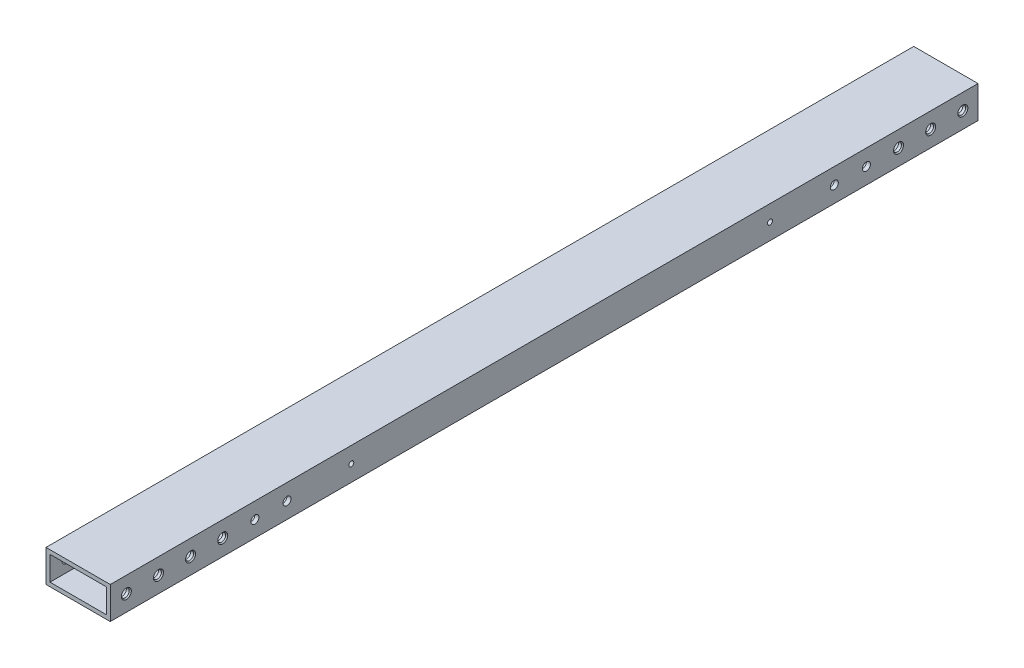
SolidWorks part; units mm, degrees
material "6061 Alloy"
ref_plane "Front Plane" through (0, 0, 0) normal (0, 0, 1) x (1, 0, 0)
ref_plane "Top Plane" through (0, 0, 0) normal (0, 1, 0) x (1, 0, 0)
ref_plane "Right Plane" through (0, 0, 0) normal (1, 0, 0) x (0, 0, -1)
sketch "Sketch1" plane through (0, 0, 0) normal (0, 0, 1) x (1, 0, 0)
  line L0 (-22.225, 9.525) -> (22.225, 9.525)
  line L2 (-25.4, 12.7) -> (25.4, 12.7)
  line L3 (-25.4, 12.7) -> (-25.4, -12.7)
  line L4 (-25.4, -12.7) -> (25.4, -12.7)
  line L5 (25.4, 12.7) -> (25.4, -12.7)
  line L10 (22.225, 9.525) -> (22.225, -9.525)
  line L11 (-22.225, -9.525) -> (22.225, -9.525)
  line L12 (-22.225, 9.525) -> (-22.225, -9.525)
  point P12 (0, 12.7)
  point P14 (25.4, 0)
  dimension "Wall Thickness" = 3.175
  dimension "Outside Width" = 50.8
  dimension "Outside Height" = 25.4
  dimension "Inside Height" = 19.05
  dimension "Inside Width" = 44.45
sketch "Sketch2" plane through (0, 0, 0) normal (1, 0, 0) x (0, 0, -1)
  line L0 (342.9, 0) -> (-342.9, 0)
  point P4 (0, 0)
  point P7 (-342.9, 0)
  point P10 (342.9, 0)
  dimension "Length" = 685.8
sketch "Sketch3" plane through (0, 0, 0) normal (0, 0, 1) x (1, 0, 0)
  line L21 (25.4, 12.7) -> (-25.4, 12.7)
  line L22 (25.4, -12.7) -> (25.4, 12.7)
  line L23 (-25.4, -12.7) -> (25.4, -12.7)
  line L24 (-25.4, 12.7) -> (-25.4, -12.7)
  line L25 (25.4, 12.7) -> (-25.4, 12.7)
  line L26 (25.4, -12.7) -> (25.4, 12.7)
  line L27 (-25.4, -12.7) -> (25.4, -12.7)
  line L28 (-25.4, 12.7) -> (-25.4, -12.7)
  line L29 (22.225, 9.525) -> (-22.225, 9.525)
  line L30 (22.225, -9.525) -> (22.225, 9.525)
  line L31 (-22.225, -9.525) -> (22.225, -9.525)
  line L32 (-22.225, 9.525) -> (-22.225, -9.525)
  line L33 (22.225, 9.525) -> (-22.225, 9.525)
  line L34 (22.225, -9.525) -> (22.225, 9.525)
  line L35 (-22.225, -9.525) -> (22.225, -9.525)
  line L36 (-22.225, 9.525) -> (-22.225, -9.525)
  dimension "D1" = 0
  dimension "D2" = 0
extrude "Boss-Extrude1" add sketch "Sketch3" along normal up to vertex (342.9 mm away) and the other way up to vertex (342.9 mm away) up to point (0, 0, 342.9) other way up to point (0, 0, -342.9)
sketch "Drawing Reference" plane through (0, 0, 0) normal (1, 0, 0) x (0, 0, -1)
  line L0 (-342.9, 0) -> (342.9, 0) construction
  line L1 (0, -12.7) -> (0, 12.7) construction
  line L2 (-342.9, -12.7) -> (342.9, -12.7) construction
  line L5 (-342.9, 12.7) -> (342.9, 12.7) construction
  point P7 (-306.324, 0)
  point P8 (306.324, 0)
  dimension "D1" = 36.576
sketch "Sketch5" plane through (25.4, 0, 0) normal (1, 0, 0) x (0, 0, -1)
  line L0 (-342.9, 0) -> (-279.4, 0)
  line L1 (-342.9, -12.7) -> (-342.9, 12.7) construction
  line L2 (-279.4, 0) -> (-254, 0)
  line L3 (-254, 0) -> (-228.6, 0)
  line L4 (-228.6, 0) -> (-203.2, 0)
sketch "Sketch8" plane through (25.4, 0, 0) normal (1, 0, 0) x (0, 0, -1)
  line L0 (342.9, 0) -> (305.5118, 0)
  line L1 (342.9, -12.7) -> (342.9, 12.7) construction
  line L2 (305.5118, 0) -> (280.1118, 0)
  line L3 (280.1118, 0) -> (254.7118, 0)
  line L4 (254.7118, 0) -> (229.3118, 0)
hole_wizard "1/4 (0.25) Diameter Hole3" positions "Sketch12" profile "Sketch13" hole size "1/4" standard "ANSI Inch" end condition through all
sketch "Sketch12" plane through (-25.4, 0, 0) normal (-1, 0, 0) x (0, 0, 1)
  point P0 (-330.9118, 0)
sketch "Sketch13" plane through (-25.4, 0, -330.9118) normal (0, 1, 0) x (0, 0, 1)
  line L0 (0, 0) -> (0, 50.8)
  line L1 (0, 50.8) -> (3.9624, 50.8)
  line L2 (3.175, 49.8942) -> (3.175, 0)
  line L5 (3.175, 0) -> (0, 0)
  line L7 (3.9624, 50.8) -> (3.175, 49.8942)
  line L8 (-3.9624, 50.8) -> (-3.175, 49.8942) construction
  line L11 (0, -6.35) -> (0, 107.95) construction
  dimension "Thru Hole Dia." = 6.35
  dimension "Thru Hole Depth" = 50.8
  dimension "Far C'Sink Dia." = 7.9248
  dimension "Far C'Sink Angle" = 82
hole_wizard "1/4 (0.25) Diameter Hole4" positions "Sketch14" profile "Sketch15" hole size "1/4" standard "ANSI Inch" end condition through all
sketch "Sketch14" plane through (-25.4, 0, 0) normal (-1, 0, 0) x (0, 0, 1)
  point P0 (304.8, 0)
  point P3 (330.2, 0)
sketch "Sketch15" plane through (-25.4, 0, 304.8) normal (0, 1, 0) x (0, 0, 1)
  line L0 (0, 0) -> (0, 50.8)
  line L1 (0, 50.8) -> (3.9624, 50.8)
  line L2 (3.175, 49.8942) -> (3.175, 0)
  line L5 (3.175, 0) -> (0, 0)
  line L7 (3.9624, 50.8) -> (3.175, 49.8942)
  line L8 (-3.9624, 50.8) -> (-3.175, 49.8942) construction
  line L11 (0, -6.35) -> (0, 107.95) construction
  dimension "Thru Hole Dia." = 6.35
  dimension "Thru Hole Depth" = 50.8
  dimension "Far C'Sink Dia." = 7.9248
  dimension "Far C'Sink Angle" = 82
hole_wizard "1/4 (0.25) Diameter Hole5" positions "Sketch17" profile "Sketch18" hole size "1/4" standard "ANSI Inch" end condition through all
sketch "Sketch17" plane through (25.4, 0, 0) normal (1, 0, 0) x (0, 0, -1)
  point P0 (305.5118, 0)
  point P3 (280.1118, 0)
sketch "Sketch18" plane through (25.4, 0, -305.5118) normal (0, 1, 0) x (0, 0, -1)
  line L0 (0, 0) -> (0, 50.8)
  line L1 (0, 50.8) -> (3.175, 50.8)
  line L2 (3.175, 50.8) -> (3.175, 0.9058)
  line L3 (3.175, 0.9058) -> (3.9624, 0)
  line L5 (3.9624, 0) -> (0, 0)
  line L6 (-3.175, 0.9058) -> (-3.9624, 0) construction
  line L11 (0, -6.35) -> (0, 107.95) construction
  dimension "Thru Hole Dia." = 6.35
  dimension "Thru Hole Depth" = 50.8
  dimension "Near C'Sink Dia." = 7.9248
  dimension "Near C'Sink Angle" = 82
hole_wizard "1/4 (0.25) Diameter Hole6" positions "Sketch19" profile "Sketch20" hole size "1/4" standard "ANSI Inch" end condition through all
sketch "Sketch19" plane through (25.4, 0, 0) normal (1, 0, 0) x (0, 0, -1)
  point P0 (229.3118, 0)
  point P3 (254.7118, 0)
sketch "Sketch20" plane through (25.4, 0, -229.3118) normal (0, 1, 0) x (0, 0, -1)
  line L0 (0, 0) -> (0, 50.8)
  line L1 (0, 50.8) -> (3.175, 50.8)
  line L2 (3.175, 50.8) -> (3.175, 0)
  line L5 (3.175, 0) -> (0, 0)
  line L11 (0, -6.35) -> (0, 107.95) construction
  dimension "Thru Hole Dia." = 6.35
  dimension "Thru Hole Depth" = 50.8
hole_wizard "1/4 (0.25) Diameter Hole7" positions "Sketch21" profile "Sketch22" hole size "1/4" standard "ANSI Inch" end condition through all
sketch "Sketch21" plane through (25.4, 0, 0) normal (1, 0, 0) x (0, 0, -1)
  point P0 (-203.2, 0)
  point P3 (-228.6, 0)
sketch "Sketch22" plane through (25.4, 0, 203.2) normal (0, 1, 0) x (0, 0, -1)
  line L0 (0, 0) -> (0, 50.8)
  line L1 (0, 50.8) -> (3.175, 50.8)
  line L2 (3.175, 50.8) -> (3.175, 0)
  line L5 (3.175, 0) -> (0, 0)
  line L11 (0, -6.35) -> (0, 107.95) construction
  dimension "Thru Hole Dia." = 6.35
  dimension "Thru Hole Depth" = 50.8
hole_wizard "1/4 (0.25) Diameter Hole8" positions "Sketch23" profile "Sketch24" hole size "1/4" standard "ANSI Inch" end condition through all
sketch "Sketch23" plane through (25.4, 0, 0) normal (1, 0, 0) x (0, 0, -1)
  point P0 (-279.4, 0)
  point P3 (-254, 0)
sketch "Sketch24" plane through (25.4, 0, 279.4) normal (0, 1, 0) x (0, 0, -1)
  line L0 (0, 0) -> (0, 50.8)
  line L1 (0, 50.8) -> (3.175, 50.8)
  line L2 (3.175, 50.8) -> (3.175, 0.9058)
  line L3 (3.175, 0.9058) -> (3.9624, 0)
  line L5 (3.9624, 0) -> (0, 0)
  line L6 (-3.175, 0.9058) -> (-3.9624, 0) construction
  line L11 (0, -6.35) -> (0, 107.95) construction
  dimension "Thru Hole Dia." = 6.35
  dimension "Thru Hole Depth" = 50.8
  dimension "Near C'Sink Dia." = 7.9248
  dimension "Near C'Sink Angle" = 82
sketch "Sketch25" plane through (25.4, 0, 0) normal (1, 0, 0) x (0, 0, -1)
  line L0 (-203.2, 0) -> (-152.4, 0)
  line L1 (229.3118, 0) -> (178.5118, 0)
  point P7 (0, 0)
hole_wizard "5/32 (0.15625) Diameter Hole1" positions "Sketch26" profile "Sketch27" hole size "5/32" standard "ANSI Inch" end condition through all
sketch "Sketch26" plane through (25.4, 0, 0) normal (1, 0, 0) x (0, 0, -1)
  point P0 (-152.4, 0)
  point P3 (178.5118, 0)
sketch "Sketch27" plane through (25.4, 0, 152.4) normal (0, 1, 0) x (0, 0, -1)
  line L0 (0, 0) -> (0, 50.8)
  line L1 (0, 50.8) -> (1.9844, 50.8)
  line L2 (1.9844, 50.8) -> (1.9844, 0)
  line L5 (1.9844, 0) -> (0, 0)
  line L11 (0, -6.35) -> (0, 107.95) construction
  dimension "Thru Hole Dia." = 3.9688
  dimension "Thru Hole Depth" = 50.8
sketch "Sketch30" plane through (-25.4, 0, 0) normal (-1, 0, 0) x (0, 0, 1)
  point P0 (-210.2618, 0)
  point P1 (152.4, 0)
equation "\"D1@Drawing Reference\"=\"Outside Width@Sketch1\" * 0.72"
